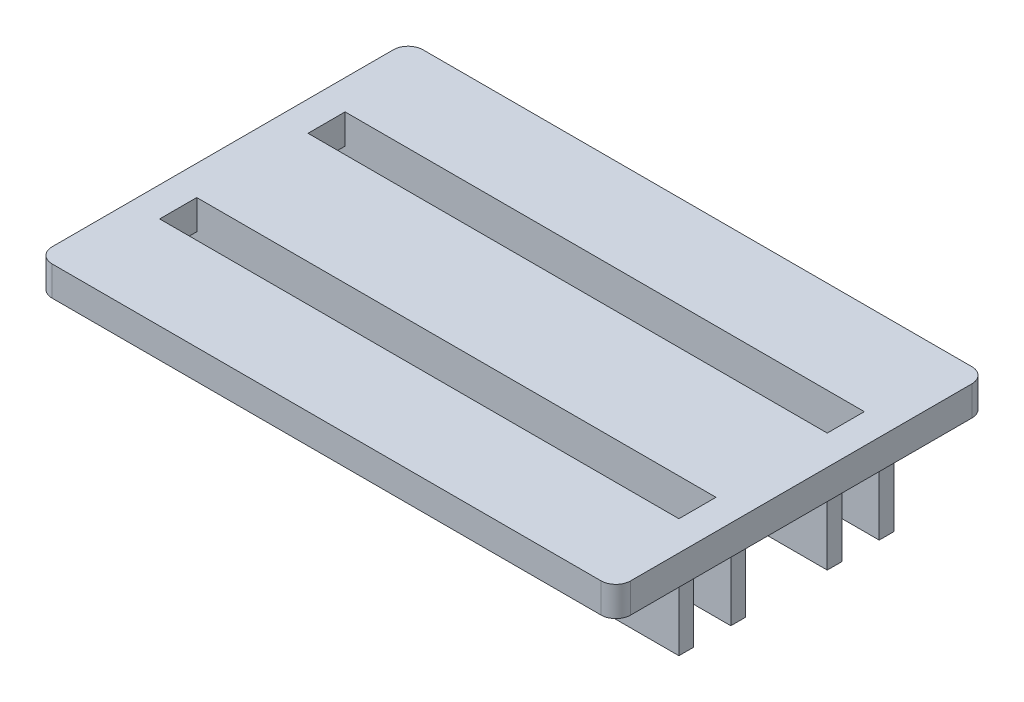
SolidWorks part; units mm, degrees
ref_plane "Front Plane" through (0, 0, 0) normal (0, 0, 1) x (1, 0, 0)
ref_plane "Top Plane" through (0, 0, 0) normal (0, 1, 0) x (1, 0, 0)
ref_plane "Right Plane" through (0, 0, 0) normal (1, 0, 0) x (0, 0, -1)
sketch "Sketch2" plane through (0, 0, 0) normal (0, 1, 0) x (1, 0, 0)
  line L1 (-46.99, 31.75) -> (46.99, 31.75)
  line L2 (-49.53, 29.21) -> (-49.53, -29.21)
  line L3 (-46.99, -31.75) -> (46.99, -31.75)
  line L4 (49.53, 29.21) -> (49.53, -29.21)
  line L5 (-49.53, 31.75) -> (49.53, -31.75) construction
  line L6 (-49.53, -31.75) -> (49.53, 31.75) construction
  arc A0 (46.99, -31.75) -> (49.53, -29.21) centre (46.99, -29.21) ccw
  arc A1 (46.99, 31.75) -> (49.53, 29.21) centre (46.99, 29.21) cw
  arc A2 (-46.99, 31.75) -> (-49.53, 29.21) centre (-46.99, 29.21) ccw
  arc A3 (-49.53, -29.21) -> (-46.99, -31.75) centre (-46.99, -29.21) ccw
  point P0 (0, 0)
  dimension "D3" = 2.54
  dimension "D1" = 63.5
  dimension "D2" = 99.06
extrude "Boss-Extrude1" add sketch "Sketch2" along normal blind 5.08
sketch "Sketch4" plane through (0, 0, 0) normal (0, 1, 0) x (1, 0, 0)
  line L0 (-49.53, 0) -> (49.53, 0) construction
  line L5 (-44.45, -9.525) -> (44.45, -15.875) construction
  line L6 (-44.45, 15.875) -> (44.45, 15.875)
  line L7 (-44.45, 15.875) -> (-44.45, 9.525)
  line L8 (-44.45, 9.525) -> (44.45, 9.525)
  line L9 (44.45, 15.875) -> (44.45, 9.525)
  line L10 (-44.45, 15.875) -> (44.45, 9.525) construction
  line L11 (-44.45, 9.525) -> (44.45, 15.875) construction
  line L12 (-44.45, -15.875) -> (44.45, -9.525) construction
  line L13 (44.45, -15.875) -> (44.45, -9.525)
  line L14 (-44.45, -9.525) -> (44.45, -9.525)
  line L15 (-44.45, -15.875) -> (-44.45, -9.525)
  line L16 (-44.45, -15.875) -> (44.45, -15.875)
  line L17 (49.53, -29.21) -> (49.53, 29.21) construction
  line L18 (-49.53, 29.21) -> (-49.53, -29.21) construction
  point P2 (0, 12.7)
  point P13 (0, -12.7)
  dimension "D1" = 88.9
  dimension "D2" = 6.35
  dimension "D3" = 25.4
extrude "Cut-Extrude2" cut sketch "Sketch4" along normal up to surface (5.08 mm away) up to face at (0, 5.08, 0)
sketch "Sketch6" plane through (0, 0, 0) normal (1, 0, 0) x (0, 0, -1)
  line L0 (0, 20.722) -> (0, -17.8578) construction
  line L1 (-15.875, 0) -> (-15.875, -12.7)
  line L2 (-15.875, -12.7) -> (-18.415, -12.7)
  line L3 (-18.415, -12.7) -> (-18.415, 0)
  line L4 (-29.21, 0) -> (29.21, 0) construction
  line L5 (-18.415, 0) -> (-15.875, 0)
  line L6 (-9.525, 0) -> (-9.525, -12.7)
  line L7 (-9.525, -12.7) -> (-6.985, -12.7)
  line L8 (-6.985, -12.7) -> (-6.985, 0)
  line L9 (-6.985, 0) -> (-9.525, 0)
  line L10 (6.985, 0) -> (9.525, 0)
  line L11 (6.985, -12.7) -> (6.985, 0)
  line L12 (9.525, -12.7) -> (6.985, -12.7)
  line L13 (9.525, 0) -> (9.525, -12.7)
  line L14 (18.415, 0) -> (15.875, 0)
  line L15 (18.415, -12.7) -> (18.415, 0)
  line L16 (15.875, -12.7) -> (18.415, -12.7)
  line L17 (15.875, 0) -> (15.875, -12.7)
  dimension "D1" = 12.7
  dimension "D2" = 2.54
  dimension "D3" = 2.54
  dimension "D4" = 12.7
extrude "Boss-Extrude2" add sketch "Sketch6" along normal mid plane 93.98
